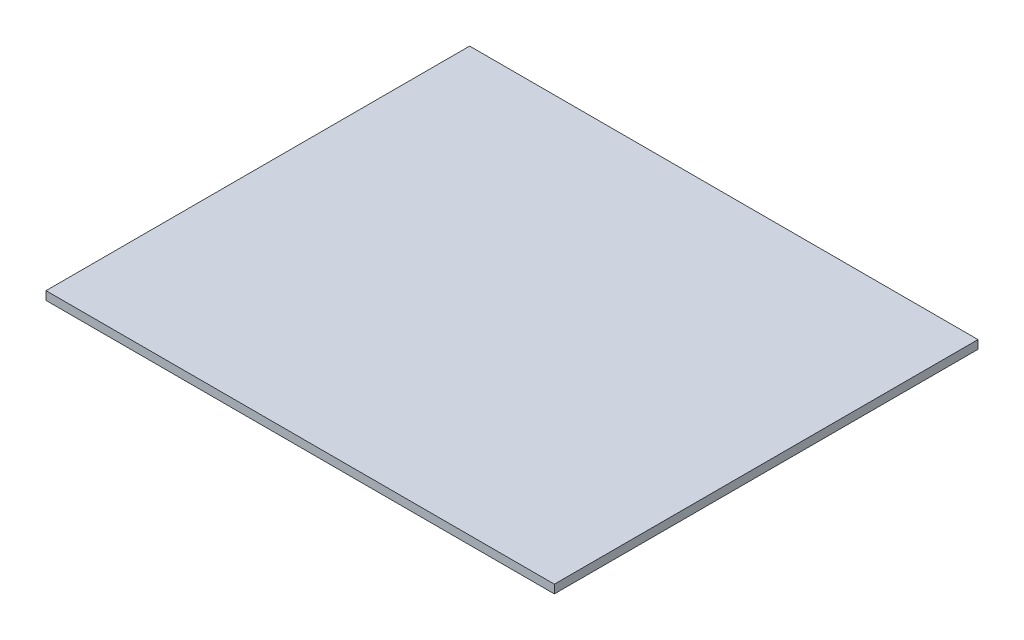
SolidWorks part; units mm, degrees
ref_plane "Front Plane" through (0, 0, 0) normal (0, 0, 1) x (1, 0, 0)
ref_plane "Top Plane" through (0, 0, 0) normal (0, 1, 0) x (1, 0, 0)
ref_plane "Right Plane" through (0, 0, 0) normal (1, 0, 0) x (0, 0, -1)
sketch "Sketch1" plane through (0, 0, 0) normal (0, 1, 0) x (1, 0, 0)
  line L1 (-300, 250) -> (300, 250)
  line L2 (-300, 250) -> (-300, -250)
  line L3 (-300, -250) -> (300, -250)
  line L4 (300, 250) -> (300, -250)
  line L5 (-300, 250) -> (300, -250) construction
  line L6 (-300, -250) -> (300, 250) construction
  point P0 (0, 0)
  dimension "D1" = 600
  dimension "D2" = 500
extrude "Boss-Extrude1" add sketch "Sketch1" along normal blind 10 contours L1 L4 L3 L2
